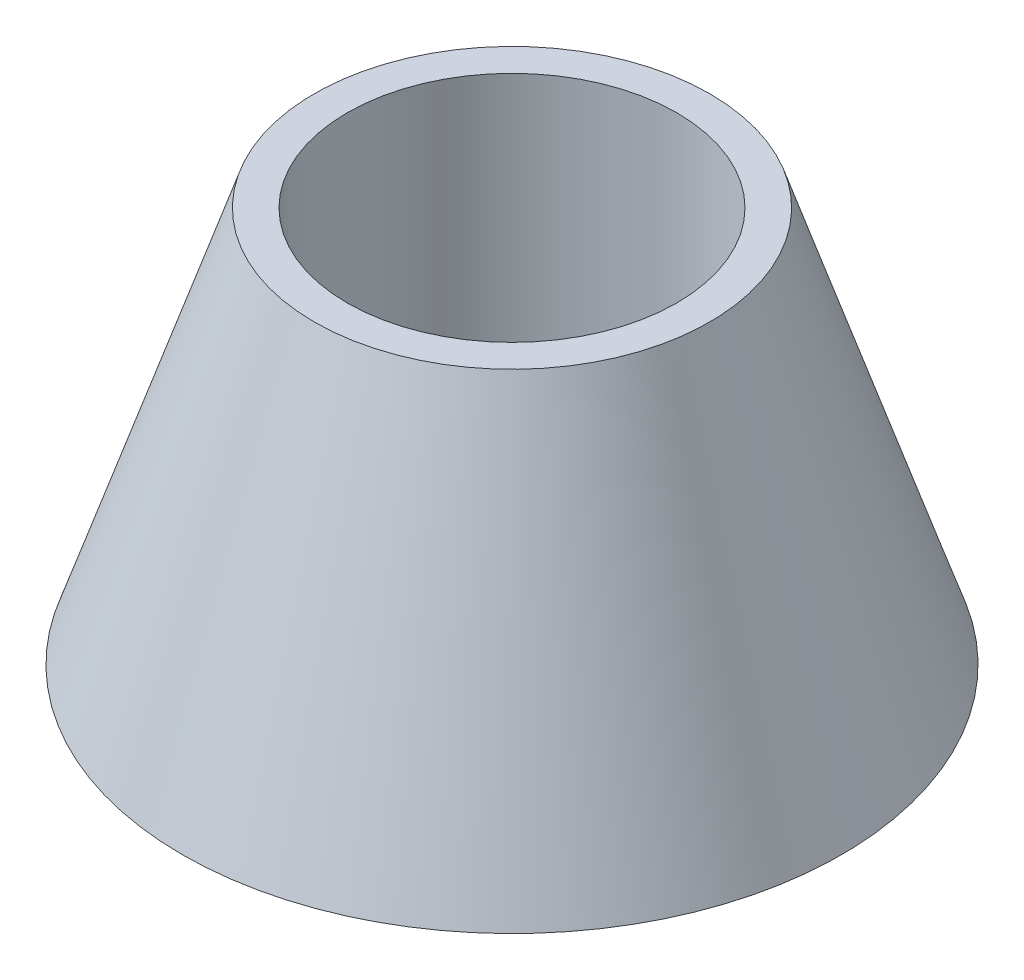
SolidWorks part; units mm, degrees
material "ABS"
ref_plane "Płaszczyzna przednia" through (0, 0, 0) normal (0, 0, 1) x (1, 0, 0)
ref_plane "Płaszczyzna górna" through (0, 0, 0) normal (0, 1, 0) x (1, 0, 0)
ref_plane "Płaszczyzna prawa" through (0, 0, 0) normal (1, 0, 0) x (0, 0, -1)
sketch "Szkic1" plane through (0, 0, 0) normal (0, 0, 1) x (1, 0, 0)
  line L0 (0, 0) -> (0, 13.3893) construction
  line L1 (5, 0.7553) -> (10, 0.7553)
  line L2 (10, 0.7553) -> (6, 12.7553)
  line L3 (6, 12.7553) -> (5, 12.7553)
  line L4 (5, 12.7553) -> (5, 0.7553)
  dimension "D1" = 5
  dimension "D2" = 12
  dimension "D3" = 1
  dimension "D4" = 5
revolve "Obrót1" add sketch "Szkic1" angle 360 about L0
